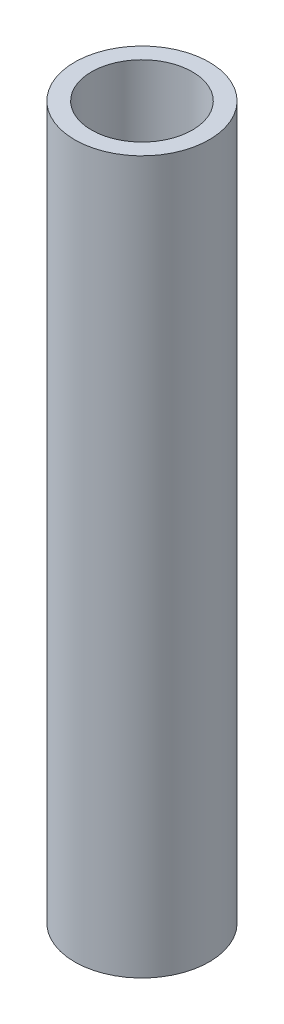
SolidWorks part; units mm, degrees
ref_plane "Front Plane" through (0, 0, 0) normal (0, 0, 1) x (1, 0, 0)
ref_plane "Top Plane" through (0, 0, 0) normal (0, 1, 0) x (1, 0, 0)
ref_plane "Right Plane" through (0, 0, 0) normal (1, 0, 0) x (0, 0, -1)
sketch "Sketch1" plane through (0, 0, 0) normal (0, 1, 0) x (1, 0, 0)
  circle A0 centre (0, 0) radius 12
extrude "Boss-Extrude1" add sketch "Sketch1" along normal blind 127 contours A0
sketch "Sketch2" plane through (0, 127, 0) normal (0, 1, 0) x (1, 0, 0)
  circle A0 centre (0, 0) radius 9
extrude "Cut-Extrude1" cut sketch "Sketch2" against normal blind 254
